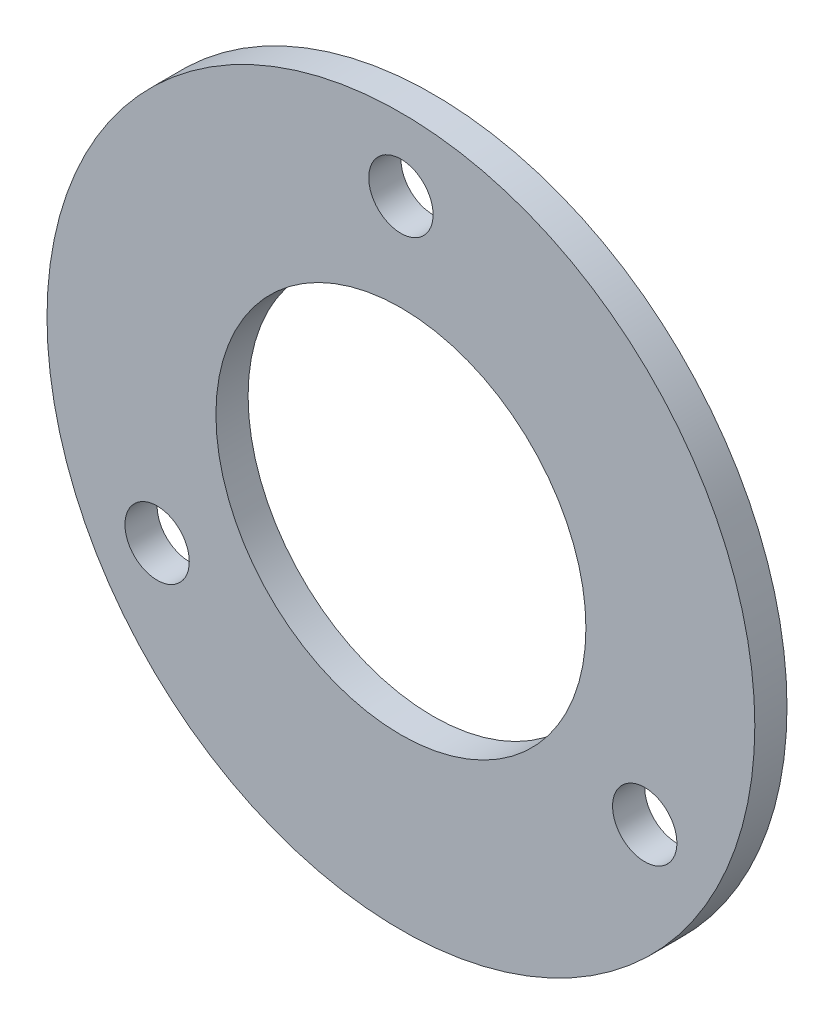
SolidWorks part; units mm, degrees
material "petg"
ref_plane "前视基准面" through (0, 0, 0) normal (0, 0, 1) x (1, 0, 0)
ref_plane "上视基准面" through (0, 0, 0) normal (0, 1, 0) x (1, 0, 0)
ref_plane "右视基准面" through (0, 0, 0) normal (1, 0, 0) x (0, 0, -1)
other "Configuration Table"
sketch "草图1" plane through (0, 0, 0) normal (0, 0, 1) x (1, 0, 0)
  circle A0 centre (0, 0) radius 22
  circle A1 centre (0, 0) radius 17.5 construction
  circle A2 centre (0, 17.5) radius 2
  circle A3 centre (15.1554, -8.75) radius 2
  circle A4 centre (-15.1554, -8.75) radius 2
  circle A5 centre (0, 0) radius 11.5
  point P12 (0, 0)
  dimension "D1" = 35
  dimension "D2" = 44
  dimension "D3" = 3
  dimension "D4" = 23
extrude "凸台-拉伸1" add sketch "草图1" along normal blind 2
